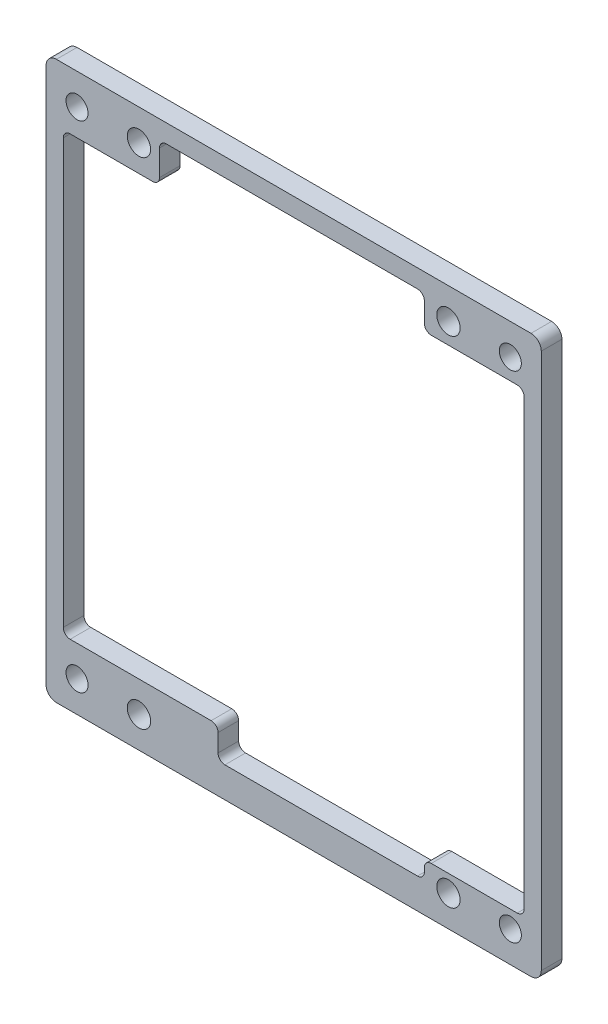
SolidWorks part; units mm, degrees
ref_plane "Alzado" through (0, 0, 0) normal (0, 0, 1) x (1, 0, 0)
ref_plane "Planta" through (0, 0, 0) normal (0, 1, 0) x (1, 0, 0)
ref_plane "Vista lateral" through (0, 0, 0) normal (1, 0, 0) x (0, 0, -1)
sketch "Model" plane through (0, 0, 0) normal (0, 0, 1) x (1, 0, 0)
  line L0 (74.6798, 300.758) -> (5.6774, 300.758)
  line L1 (76.1798, 221.2534) -> (76.1798, 299.258)
  line L2 (5.6774, 219.7534) -> (74.6798, 219.7534)
  line L3 (4.1774, 299.258) -> (4.1774, 221.2534)
  line L4 (73.6796, 292.2602) -> (73.6796, 227.7556)
  line L5 (6.6772, 291.3702) -> (6.6772, 229.73)
  line L6 (58.1796, 298.0971) -> (21.6772, 298.0971)
  line L7 (58.1796, 224.1656) -> (30.1772, 224.1656)
  line L8 (59.1796, 297.0971) -> (59.1796, 294.2602)
  line L9 (60.1796, 293.2602) -> (72.6796, 293.2602)
  line L10 (7.6772, 292.3702) -> (19.6772, 292.3702)
  line L11 (20.6772, 293.3702) -> (20.6772, 297.0971)
  line L12 (29.1772, 225.1656) -> (29.1772, 227.73)
  line L13 (28.1772, 228.73) -> (7.6772, 228.73)
  line L14 (72.6796, 226.7556) -> (60.1796, 226.7556)
  line L15 (59.1796, 225.1656) -> (59.1796, 225.7556)
  arc A0 (5.6774, 300.758) -> (4.1774, 299.258) centre (5.6774, 299.258) ccw
  arc A1 (4.1774, 221.2534) -> (5.6774, 219.7534) centre (5.6774, 221.2534) ccw
  arc A2 (74.6798, 219.7534) -> (76.1798, 221.2534) centre (74.6798, 221.2534) ccw
  arc A3 (76.1798, 299.258) -> (74.6798, 300.758) centre (74.6798, 299.258) ccw
  circle A4 centre (17.6767, 224.2531) radius 1.7
  circle A5 centre (62.6801, 224.2531) radius 1.7
  circle A6 centre (8.6771, 224.2531) radius 1.6003
  circle A7 centre (71.6798, 224.2531) radius 1.6003
  circle A8 centre (17.6767, 296.258) radius 1.7
  circle A9 centre (62.6801, 296.258) radius 1.7
  circle A10 centre (71.6798, 296.258) radius 1.6003
  circle A11 centre (8.6771, 296.258) radius 1.6003
  arc A12 (21.6772, 298.0971) -> (20.6772, 297.0971) centre (21.6772, 297.0971) ccw
  arc A13 (19.6772, 292.3702) -> (20.6772, 293.3702) centre (19.6772, 293.3702) ccw
  arc A14 (7.6772, 292.3702) -> (6.6772, 291.3702) centre (7.6772, 291.3702) ccw
  arc A15 (29.1772, 227.73) -> (28.1772, 228.73) centre (28.1772, 227.73) ccw
  arc A16 (29.1772, 225.1656) -> (30.1772, 224.1656) centre (30.1772, 225.1656) ccw
  arc A17 (59.1796, 297.0971) -> (58.1796, 298.0971) centre (58.1796, 297.0971) ccw
  arc A18 (59.1796, 294.2602) -> (60.1796, 293.2602) centre (60.1796, 294.2602) ccw
  arc A19 (73.6796, 292.2602) -> (72.6796, 293.2602) centre (72.6796, 292.2602) ccw
  arc A20 (60.1796, 226.7556) -> (59.1796, 225.7556) centre (60.1796, 225.7556) ccw
  arc A21 (72.6796, 226.7556) -> (73.6796, 227.7556) centre (72.6796, 227.7556) ccw
  arc A22 (58.1796, 224.1656) -> (59.1796, 225.1656) centre (58.1796, 225.1656) ccw
  arc A23 (6.6772, 229.73) -> (7.6772, 228.73) centre (7.6772, 229.73) ccw
extrude "Saliente-Extruir1" add sketch "Model" along normal blind 3
